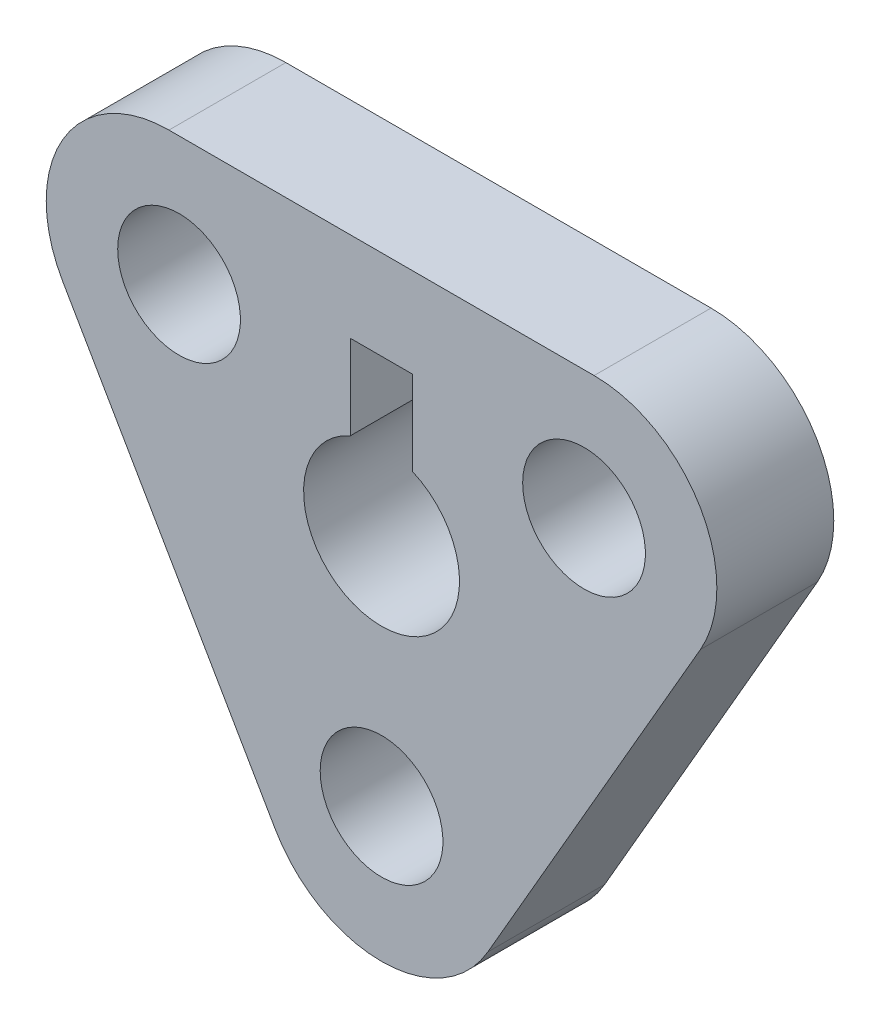
SolidWorks part; units mm, degrees
ref_plane "Front Plane" through (0, 0, 0) normal (0, 0, 1) x (1, 0, 0)
ref_plane "Top Plane" through (0, 0, 0) normal (0, 1, 0) x (1, 0, 0)
ref_plane "Right Plane" through (0, 0, 0) normal (1, 0, 0) x (0, 0, -1)
sketch "Sketch2" plane through (0, 0, 0) normal (0, 0, 1) x (1, 0, 0)
  line L0 (0, 0) -> (0, -40) construction
  line L1 (0, 0) -> (-34.641, 20) construction
  line L2 (0, 0) -> (34.641, 20) construction
  line L3 (-34.641, 20) -> (0, -40)
  line L4 (0, -40) -> (34.641, 20)
  line L5 (34.641, 20) -> (-34.641, 20)
  circle A1 centre (0, 0) radius 6.35
  circle A2 centre (-16.4978, 9.525) radius 5
  circle A3 centre (16.4978, 9.525) radius 5
  circle A4 centre (0, -19.05) radius 5
  point P13 (0, 0)
  point P15 (0, 0)
  dimension "D1" = 12.7
  dimension "D2" = 10
  dimension "D4" = 3
  dimension "D5" = 3
  dimension "D3" = 19.05
  dimension "D6" = 40
extrude "Boss-Extrude1" add sketch "Sketch2" along normal blind 9.525
fillet "Fillet1" radius 10 3 edges at (0, -40, 4.7625) (-34.641, 20, 4.7625) (34.641, 20, 4.7625)
sketch "Sketch3" plane through (0, 0, 0) normal (0, 0, 1) x (1, 0, 0)
  line L0 (0, -5.2388) -> (0, 5.2388) construction
  line L1 (-2.54, 12.7) -> (2.54, 12.7)
  line L2 (-2.54, 12.7) -> (-2.54, 0)
  line L3 (-2.54, 0) -> (2.54, 0)
  line L4 (2.54, 12.7) -> (2.54, 0)
  line L5 (-2.54, 6.35) -> (2.54, 6.35) construction
  circle A0 centre (0, 0) radius 6.35 construction
  point P4 (0, 0)
  dimension "D1" = 12.7
  dimension "D2" = 5.08
extrude "Cut-Extrude1" cut sketch "Sketch3" along normal through all
